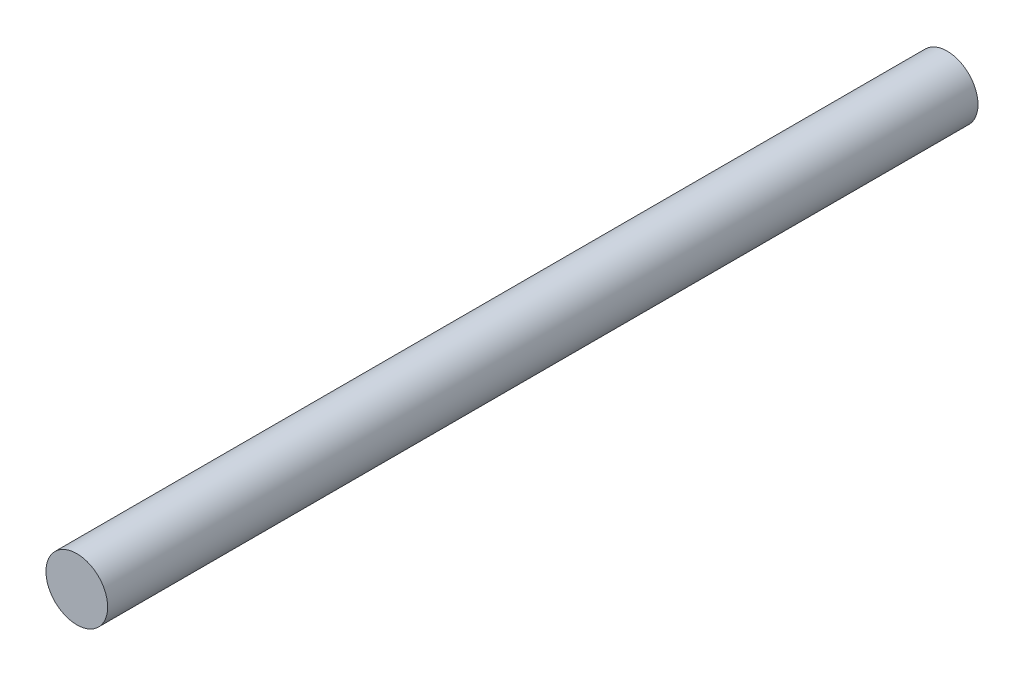
SolidWorks part; units mm, degrees
ref_plane "Plan de face" through (0, 0, 0) normal (0, 0, 1) x (1, 0, 0)
ref_plane "Plan de dessus" through (0, 0, 0) normal (0, 1, 0) x (1, 0, 0)
ref_plane "Plan de droite" through (0, 0, 0) normal (1, 0, 0) x (0, 0, -1)
sketch "Esquisse1" plane through (0, 0, 0) normal (0, 0, 1) x (1, 0, 0)
  circle A0 centre (0, 0) radius 5
  dimension "D1" = 10
extrude "Boss.-Extru.1" add sketch "Esquisse1" along normal blind 141
